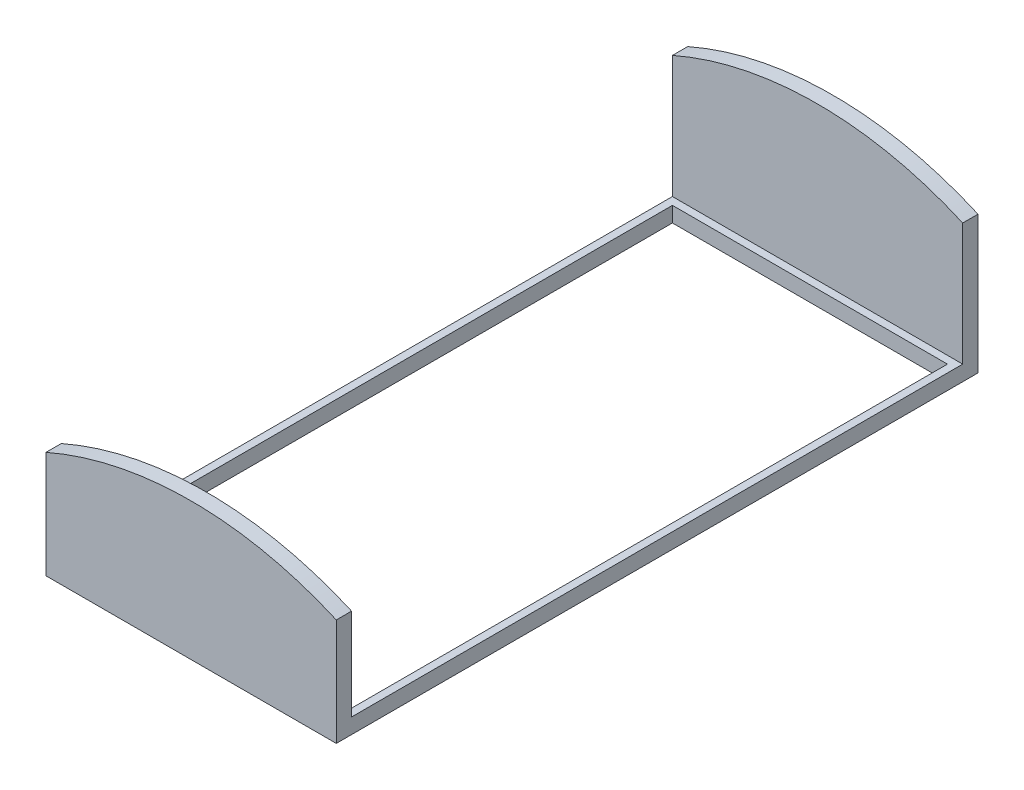
SolidWorks part; units mm, degrees
ref_plane "Alzado" through (0, 0, 0) normal (0, 0, 1) x (1, 0, 0)
ref_plane "Planta" through (0, 0, 0) normal (0, 1, 0) x (1, 0, 0)
ref_plane "Vista lateral" through (0, 0, 0) normal (1, 0, 0) x (0, 0, -1)
sketch "Croquis1" plane through (0, 0, 0) normal (0, 1, 0) x (1, 0, 0)
  line L1 (-475, -1000) -> (475, -1000)
  line L2 (-475, -1000) -> (-475, 1000)
  line L3 (-475, 1000) -> (475, 1000)
  line L4 (475, -1000) -> (475, 1000)
  line L5 (-475, -1000) -> (475, 1000) construction
  line L6 (-475, 1000) -> (475, -1000) construction
  line L7 (-450, -975) -> (450, -975)
  line L8 (-450, -975) -> (-450, 975)
  line L9 (-450, 975) -> (450, 975)
  line L10 (450, -975) -> (450, 975)
  line L11 (-450, -975) -> (450, 975) construction
  line L12 (-450, 975) -> (450, -975) construction
  point P0 (0, 0)
  point P6 (0, 0)
  dimension "D1" = 950
  dimension "D2" = 2000
  dimension "D3" = 900
  dimension "D4" = 1950
extrude "Saliente-Extruir1" add sketch "Croquis1" along normal blind 50
sketch "Croquis3" plane through (0, 0, -1000) normal (0, 0, -1) x (-1, 0, 0)
  line L1 (-475, 0) -> (475, 0)
  line L2 (-475, 0) -> (-475, 50)
  line L3 (-475, 50) -> (475, 50)
  line L4 (475, 0) -> (475, 50)
extrude "Saliente-Extruir3" add sketch "Croquis3" along normal blind 50
sketch "Croquis4" plane through (0, 50, 0) normal (0, 1, 0) x (1, 0, 0)
  line L0 (475, -1000) -> (475, 1050) construction
  line L1 (-475, 1050) -> (475, 1050)
  line L2 (-475, 1050) -> (-475, 1000)
  line L3 (-475, 1000) -> (475, 1000)
  line L5 (475, 1050) -> (475, 1000)
  line L29 (-475, 1050) -> (-427, 1050) construction
  dimension "D1" = 50
  dimension "D3" = 48
sketch "Croquis6" plane through (0, 0, 1000) normal (0, 0, 1) x (1, 0, 0)
  line L1 (-475, 0) -> (475, 0)
  line L2 (-475, 0) -> (-475, 50)
  line L3 (-475, 50) -> (475, 50)
  line L4 (475, 0) -> (475, 50)
extrude "Saliente-Extruir6" add sketch "Croquis6" along normal blind 50
extrude "Saliente-Extruir7" add sketch "Croquis4" along normal blind 400
sketch "Croquis8" plane through (0, 0, -1050) normal (0, 0, -1) x (-1, 0, 0)
  line L0 (-475, 450) -> (475, 450)
  line L1 (0, 450) -> (0, 550) construction
  arc A1 (-475, 450) -> (475, 450) centre (0, -627.919) cw
  dimension "D2" = 1177.9365
  dimension "D1" = 100
extrude "Saliente-Extruir8" add sketch "Croquis8" against normal blind 50
sketch "Croquis9" plane through (0, 50, 0) normal (0, 1, 0) x (1, 0, 0)
  line L0 (475, -1050) -> (475, 1000) construction
  line L1 (-475, -1050) -> (475, -1050)
  line L2 (-475, -1050) -> (-475, -1000)
  line L3 (-475, -1000) -> (475, -1000)
  line L4 (475, -1050) -> (475, -1000)
  dimension "D1" = 50
extrude "Saliente-Extruir9" add sketch "Croquis9" along normal blind 300
sketch "Croquis10" plane through (0, 0, 1050) normal (0, 0, 1) x (1, 0, 0)
  line L0 (-475, 350) -> (475, 350)
  line L1 (0, 350) -> (0, 450) construction
  arc A0 (-475, 350) -> (475, 350) centre (0, -728.6257) cw
  dimension "D2" = 1178.5833
  dimension "D1" = 100
extrude "Saliente-Extruir10" add sketch "Croquis10" against normal blind 50
